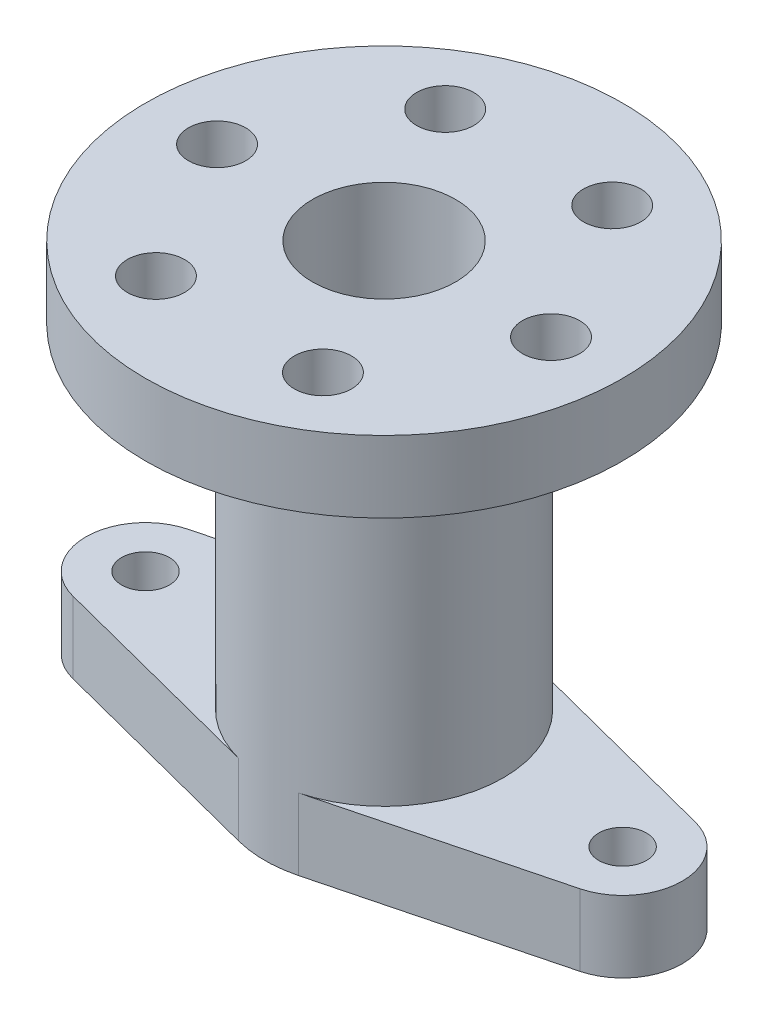
SolidWorks part; units mm, degrees
ref_plane "Front Plane" through (0, 0, 0) normal (0, 0, 1) x (1, 0, 0)
ref_plane "Top Plane" through (0, 0, 0) normal (0, 1, 0) x (1, 0, 0)
ref_plane "Right Plane" through (0, 0, 0) normal (1, 0, 0) x (0, 0, -1)
sketch "Sketch1" plane through (0, 0, 0) normal (0, 1, 0) x (1, 0, 0)
  line L0 (-72.1635, 0) -> (129.0386, 0) construction
  line L1 (0, 0) -> (0, 49.7511) construction
  line L2 (-53.125, 12.1031) -> (-6.25, 24.2061)
  line L3 (53.125, 12.1031) -> (6.25, 24.2061)
  line L4 (53.125, -12.1031) -> (6.25, -24.2061)
  line L5 (-53.125, -12.1031) -> (-6.25, -24.2061)
  arc A0 (-53.125, 12.1031) -> (-53.125, -12.1031) centre (-50, 0) ccw
  arc A1 (53.125, -12.1031) -> (53.125, 12.1031) centre (50, 0) ccw
  arc A2 (-6.25, -24.2061) -> (6.25, -24.2061) centre (0, 0) ccw
  arc A3 (6.25, 24.2061) -> (-6.25, 24.2061) centre (0, 0) ccw
  dimension "D1" = 25
  dimension "D3" = 50
  dimension "D2" = 100
extrude "Boss-Extrude1" add sketch "Sketch1" along normal blind 15
sketch "Sketch2" plane through (0, 15, 0) normal (0, 1, 0) x (1, 0, 0)
  circle A0 centre (0, 0) radius 25
  arc A1 (6.25, 24.2061) -> (-6.25, 24.2061) centre (0, 0) ccw construction
extrude "Boss-Extrude2" add sketch "Sketch2" along normal blind 70
sketch "Sketch3" plane through (0, 85, 0) normal (0, 1, 0) x (1, 0, 0)
  circle A0 centre (0, 0) radius 50
  dimension "D1" = 100
extrude "Boss-Extrude3" add sketch "Sketch3" along normal blind 15
hole_wizard "Hole1" positions "Sketch6" profile "Sketch5" legacy end condition through all
sketch "Sketch6" plane through (0, 100, 0) normal (0, 1, 0) x (1, 0, 0)
  point P0 (0, 0)
sketch "Sketch5" plane through (0, 100, 0) normal (1, 0, 0) x (0, 0, 1)
  line L0 (0, 0) -> (0, 100)
  line L1 (0, 100) -> (15, 100)
  line L2 (15, 100) -> (15, 0)
  line L3 (15, 0) -> (0, 0)
  line L4 (0, 110) -> (0, -10) construction
  dimension "Diameter" = 30
  dimension "Depth" = 100
hole_wizard "Hole2" positions "Sketch9" profile "Sketch8" legacy
sketch "Sketch9" plane through (0, 100, 0) normal (0, 1, 0) x (1, 0, 0)
  point P0 (35, 0)
  point P4 (0, 0)
  dimension "D1" = 35
sketch "Sketch8" plane through (35, 100, 0) normal (1, 0, 0) x (0, 0, 1)
  line L0 (0, 0) -> (0, 15)
  line L1 (0, 15) -> (6, 15)
  line L2 (6, 15) -> (6, 0)
  line L3 (6, 0) -> (0, 0)
  line L4 (0, 110) -> (0, -10) construction
  dimension "Diameter" = 12
  dimension "Depth" = 15
pattern_circular "CirPattern1" count 6 over 360 about axis through (0, 0, 0) along (0, 1, 0) of "Hole2"
hole_wizard "Hole3" positions "Sketch12" profile "Sketch13" legacy
sketch "Sketch12" plane through (0, 0, 0) normal (0, -1, 0) x (-1, 0, 0)
  point P0 (50, 0)
  point P3 (-50, 0)
sketch "Sketch13" plane through (-50, 0, 0) normal (1, 0, 0) x (0, 0, -1)
  line L0 (0, 0) -> (0, 15)
  line L1 (0, 15) -> (5, 15)
  line L2 (5, 15) -> (5, 0)
  line L3 (5, 0) -> (0, 0)
  line L4 (0, 110) -> (0, -10) construction
  dimension "Diameter" = 10
  dimension "Depth" = 15
